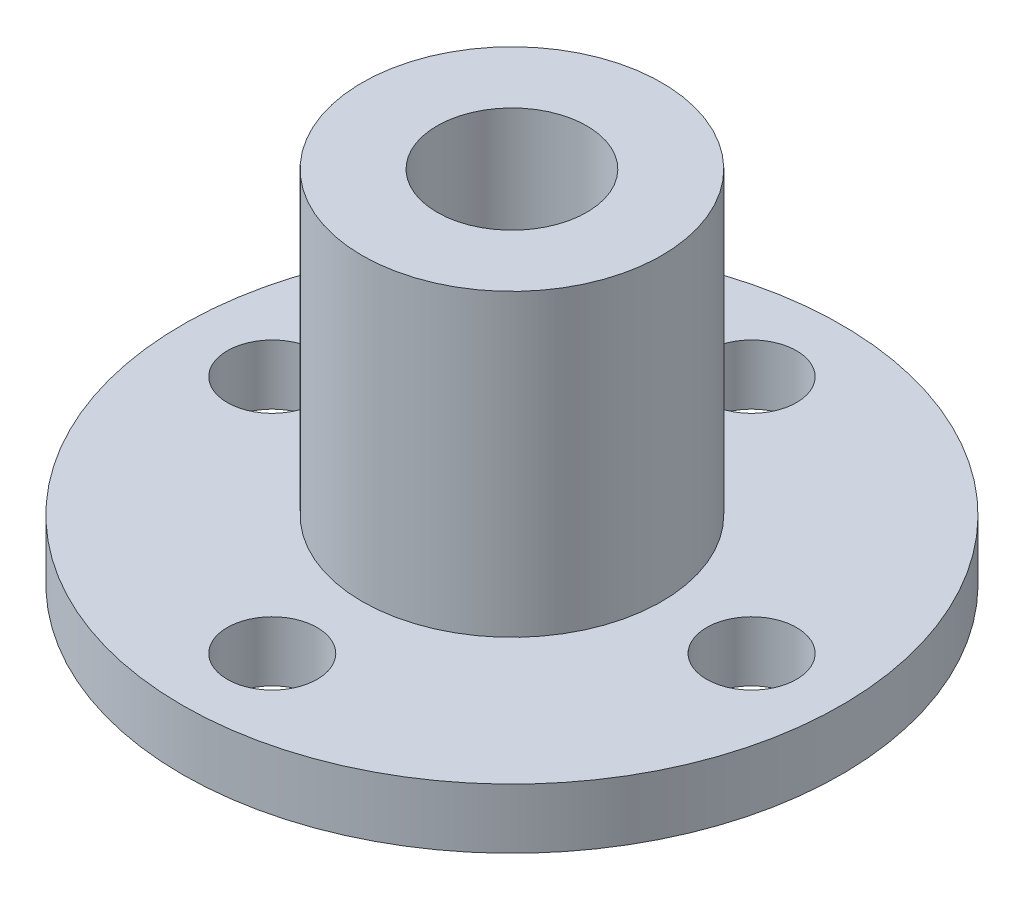
SolidWorks part; units mm, degrees
ref_plane "Front Plane" through (0, 0, 0) normal (0, 0, 1) x (1, 0, 0)
ref_plane "Top Plane" through (0, 0, 0) normal (0, 1, 0) x (1, 0, 0)
ref_plane "Right Plane" through (0, 0, 0) normal (1, 0, 0) x (0, 0, -1)
sketch "Sketch1" plane through (0, 0, 0) normal (0, 1, 0) x (1, 0, 0)
  circle A0 centre (0, 0) radius 11
  circle A1 centre (0, 8) radius 1.5
  circle A2 centre (8, 0) radius 1.5
  circle A3 centre (0, -8) radius 1.5
  circle A4 centre (-8, 0) radius 1.5
  circle A5 centre (0, 0) radius 2.5
  point P14 (0, 0)
  dimension "D1" = 3
  dimension "D3" = 22
  dimension "D5" = 5
  dimension "D2" = 8
  dimension "D4" = 4
extrude "Boss-Extrude1" add sketch "Sketch1" along normal blind 2
sketch "Sketch2" plane through (0, 2, 0) normal (0, 1, 0) x (1, 0, 0)
  circle A0 centre (0, 0) radius 2.5
  circle A1 centre (0, 0) radius 5
  dimension "D1" = 10
extrude "Boss-Extrude2" add sketch "Sketch2" along normal blind 10
